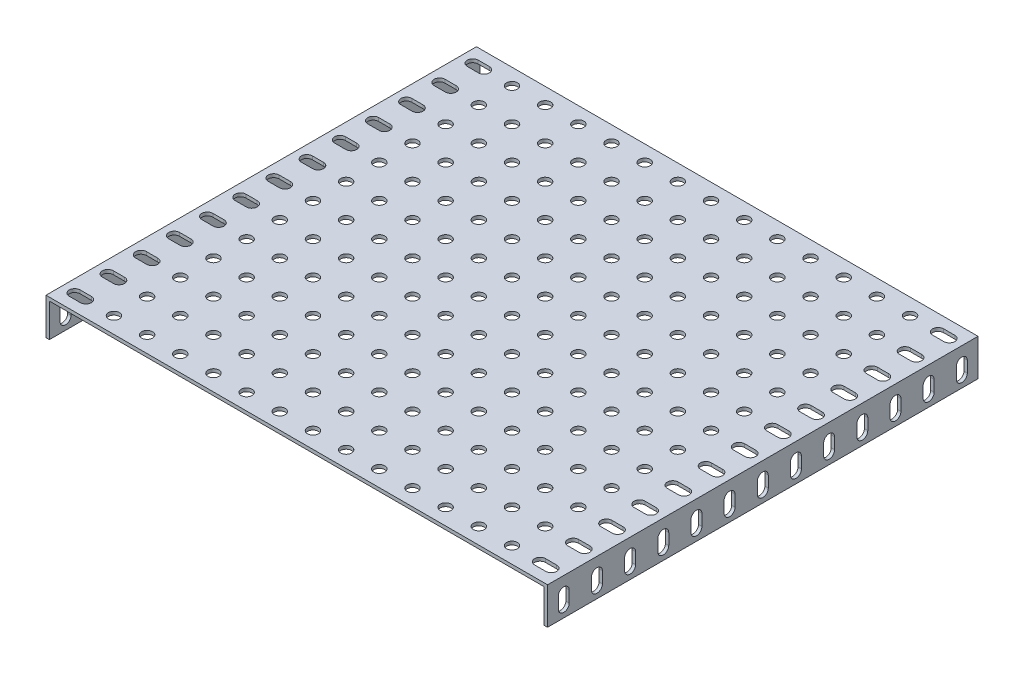
SolidWorks part; units mm, degrees
ref_plane "Front Plane" through (0, 0, 0) normal (0, 0, 1) x (1, 0, 0)
ref_plane "Top Plane" through (0, 0, 0) normal (0, 1, 0) x (1, 0, 0)
ref_plane "Right Plane" through (0, 0, 0) normal (1, 0, 0) x (0, 0, -1)
sketch "Sketch1" plane through (0, 0, 0) normal (0, 1, 0) x (1, 0, 0)
  line L0 (0, -76.56) -> (0, 76.56) construction
  line L1 (-91.66, 76.56) -> (-87.36, 76.56) construction
  line L2 (-91.66, 78.67) -> (-87.36, 78.67)
  line L3 (-91.66, 74.45) -> (-87.36, 74.45)
  line L4 (-91.66, 63.8) -> (-87.36, 63.8) construction
  line L5 (-91.66, 65.91) -> (-87.36, 65.91)
  line L6 (-91.66, 61.69) -> (-87.36, 61.69)
  line L7 (-91.66, 51.04) -> (-87.36, 51.04) construction
  line L8 (-91.66, 53.15) -> (-87.36, 53.15)
  line L9 (-91.66, 48.93) -> (-87.36, 48.93)
  line L10 (-91.66, 38.28) -> (-87.36, 38.28) construction
  line L11 (-91.66, 40.39) -> (-87.36, 40.39)
  line L12 (-91.66, 36.17) -> (-87.36, 36.17)
  line L13 (-91.66, 25.52) -> (-87.36, 25.52) construction
  line L14 (-91.66, 27.63) -> (-87.36, 27.63)
  line L15 (-91.66, 23.41) -> (-87.36, 23.41)
  line L16 (-91.66, 12.76) -> (-87.36, 12.76) construction
  line L17 (-91.66, 14.87) -> (-87.36, 14.87)
  line L18 (-91.66, 10.65) -> (-87.36, 10.65)
  line L19 (-91.66, 0) -> (-87.36, 0) construction
  line L20 (-91.66, 2.11) -> (-87.36, 2.11)
  line L21 (-91.66, -2.11) -> (-87.36, -2.11)
  line L22 (-91.66, -12.76) -> (-87.36, -12.76) construction
  line L23 (-91.66, -10.65) -> (-87.36, -10.65)
  line L24 (-91.66, -14.87) -> (-87.36, -14.87)
  line L25 (-91.66, -25.52) -> (-87.36, -25.52) construction
  line L26 (-91.66, -23.41) -> (-87.36, -23.41)
  line L27 (-91.66, -27.63) -> (-87.36, -27.63)
  line L28 (-91.66, -38.28) -> (-87.36, -38.28) construction
  line L29 (-91.66, -36.17) -> (-87.36, -36.17)
  line L30 (-91.66, -40.39) -> (-87.36, -40.39)
  line L31 (-91.66, -51.04) -> (-87.36, -51.04) construction
  line L32 (-91.66, -48.93) -> (-87.36, -48.93)
  line L33 (-91.66, -53.15) -> (-87.36, -53.15)
  line L34 (-91.66, -63.8) -> (-87.36, -63.8) construction
  line L35 (-91.66, -61.69) -> (-87.36, -61.69)
  line L36 (-91.66, -65.91) -> (-87.36, -65.91)
  line L37 (-91.66, -76.56) -> (-87.36, -76.56) construction
  line L38 (-91.66, -74.45) -> (-87.36, -74.45)
  line L39 (-91.66, -78.67) -> (-87.36, -78.67)
  line L40 (91.66, 76.56) -> (87.36, 76.56) construction
  line L41 (91.66, 78.67) -> (87.36, 78.67)
  line L42 (91.66, 74.45) -> (87.36, 74.45)
  line L43 (91.66, 63.8) -> (87.36, 63.8) construction
  line L44 (91.66, 65.91) -> (87.36, 65.91)
  line L45 (91.66, 61.69) -> (87.36, 61.69)
  line L46 (91.66, 51.04) -> (87.36, 51.04) construction
  line L47 (91.66, 53.15) -> (87.36, 53.15)
  line L48 (91.66, 48.93) -> (87.36, 48.93)
  line L49 (91.66, 38.28) -> (87.36, 38.28) construction
  line L50 (91.66, 40.39) -> (87.36, 40.39)
  line L51 (91.66, 36.17) -> (87.36, 36.17)
  line L52 (91.66, 25.52) -> (87.36, 25.52) construction
  line L53 (91.66, 27.63) -> (87.36, 27.63)
  line L54 (91.66, 23.41) -> (87.36, 23.41)
  line L55 (91.66, 12.76) -> (87.36, 12.76) construction
  line L56 (91.66, 14.87) -> (87.36, 14.87)
  line L57 (91.66, 10.65) -> (87.36, 10.65)
  line L58 (91.66, 0) -> (87.36, 0) construction
  line L59 (91.66, 2.11) -> (87.36, 2.11)
  line L60 (91.66, -2.11) -> (87.36, -2.11)
  line L61 (91.66, -12.76) -> (87.36, -12.76) construction
  line L62 (91.66, -10.65) -> (87.36, -10.65)
  line L63 (91.66, -14.87) -> (87.36, -14.87)
  line L64 (91.66, -25.52) -> (87.36, -25.52) construction
  line L65 (91.66, -23.41) -> (87.36, -23.41)
  line L66 (91.66, -27.63) -> (87.36, -27.63)
  line L67 (91.66, -38.28) -> (87.36, -38.28) construction
  line L68 (91.66, -36.17) -> (87.36, -36.17)
  line L69 (91.66, -40.39) -> (87.36, -40.39)
  line L70 (91.66, -51.04) -> (87.36, -51.04) construction
  line L71 (91.66, -48.93) -> (87.36, -48.93)
  line L72 (91.66, -53.15) -> (87.36, -53.15)
  line L73 (91.66, -63.8) -> (87.36, -63.8) construction
  line L74 (91.66, -61.69) -> (87.36, -61.69)
  line L75 (91.66, -65.91) -> (87.36, -65.91)
  line L76 (91.66, -76.56) -> (87.36, -76.56) construction
  line L77 (91.66, -74.45) -> (87.36, -74.45)
  line L78 (91.66, -78.67) -> (87.36, -78.67)
  line L80 (-93.77, 51.04) -> (-96.47, 51.04) construction
  line L81 (-96.47, 51.04) -> (-96.47, 82.79) construction
  line L83 (91.66, -78.67) -> (91.66, -82.79) construction
  line L84 (91.66, -82.79) -> (96.47, -82.79) construction
  line L86 (-96.47, 82.79) -> (96.47, 82.79)
  line L87 (-96.47, 82.79) -> (-96.47, -82.79)
  line L88 (-96.47, -82.79) -> (96.47, -82.79)
  line L89 (96.47, 82.79) -> (96.47, -82.79)
  circle A0 centre (-76.56, -76.56) radius 2.11
  circle A1 centre (-63.8, -76.56) radius 2.11
  circle A2 centre (-51.04, -76.56) radius 2.11
  circle A3 centre (-38.28, -76.56) radius 2.11
  circle A4 centre (-25.52, -76.56) radius 2.11
  circle A5 centre (-12.76, -76.56) radius 2.11
  circle A6 centre (0, -76.56) radius 2.11
  circle A7 centre (12.76, -76.56) radius 2.11
  circle A8 centre (25.52, -76.56) radius 2.11
  circle A9 centre (38.28, -76.56) radius 2.11
  circle A10 centre (51.04, -76.56) radius 2.11
  circle A11 centre (63.8, -76.56) radius 2.11
  circle A12 centre (76.56, -76.56) radius 2.11
  circle A13 centre (-63.8, -63.8) radius 2.11
  circle A14 centre (-51.04, -63.8) radius 2.11
  circle A15 centre (-38.28, -63.8) radius 2.11
  circle A16 centre (-25.52, -63.8) radius 2.11
  circle A17 centre (-12.76, -63.8) radius 2.11
  circle A18 centre (0, -63.8) radius 2.11
  circle A19 centre (12.76, -63.8) radius 2.11
  circle A20 centre (25.52, -63.8) radius 2.11
  circle A21 centre (38.28, -63.8) radius 2.11
  circle A22 centre (51.04, -63.8) radius 2.11
  circle A23 centre (63.8, -63.8) radius 2.11
  circle A24 centre (76.56, -63.8) radius 2.11
  circle A25 centre (-63.8, -51.04) radius 2.11
  circle A26 centre (-51.04, -51.04) radius 2.11
  circle A27 centre (-38.28, -51.04) radius 2.11
  circle A28 centre (-25.52, -51.04) radius 2.11
  circle A29 centre (-12.76, -51.04) radius 2.11
  circle A30 centre (0, -51.04) radius 2.11
  circle A31 centre (12.76, -51.04) radius 2.11
  circle A32 centre (25.52, -51.04) radius 2.11
  circle A33 centre (38.28, -51.04) radius 2.11
  circle A34 centre (51.04, -51.04) radius 2.11
  circle A35 centre (63.8, -51.04) radius 2.11
  circle A36 centre (76.56, -51.04) radius 2.11
  circle A37 centre (-63.8, -38.28) radius 2.11
  circle A38 centre (-51.04, -38.28) radius 2.11
  circle A39 centre (-38.28, -38.28) radius 2.11
  circle A40 centre (-25.52, -38.28) radius 2.11
  circle A41 centre (-12.76, -38.28) radius 2.11
  circle A42 centre (0, -38.28) radius 2.11
  circle A43 centre (12.76, -38.28) radius 2.11
  circle A44 centre (25.52, -38.28) radius 2.11
  circle A45 centre (38.28, -38.28) radius 2.11
  circle A46 centre (51.04, -38.28) radius 2.11
  circle A47 centre (63.8, -38.28) radius 2.11
  circle A48 centre (76.56, -38.28) radius 2.11
  circle A49 centre (-63.8, -25.52) radius 2.11
  circle A50 centre (-51.04, -25.52) radius 2.11
  circle A51 centre (-38.28, -25.52) radius 2.11
  circle A52 centre (-25.52, -25.52) radius 2.11
  circle A53 centre (-12.76, -25.52) radius 2.11
  circle A54 centre (0, -25.52) radius 2.11
  circle A55 centre (12.76, -25.52) radius 2.11
  circle A56 centre (25.52, -25.52) radius 2.11
  circle A57 centre (38.28, -25.52) radius 2.11
  circle A58 centre (51.04, -25.52) radius 2.11
  circle A59 centre (63.8, -25.52) radius 2.11
  circle A60 centre (76.56, -25.52) radius 2.11
  circle A61 centre (-63.8, -12.76) radius 2.11
  circle A62 centre (-51.04, -12.76) radius 2.11
  circle A63 centre (-38.28, -12.76) radius 2.11
  circle A64 centre (-25.52, -12.76) radius 2.11
  circle A65 centre (-12.76, -12.76) radius 2.11
  circle A66 centre (0, -12.76) radius 2.11
  circle A67 centre (12.76, -12.76) radius 2.11
  circle A68 centre (25.52, -12.76) radius 2.11
  circle A69 centre (38.28, -12.76) radius 2.11
  circle A70 centre (51.04, -12.76) radius 2.11
  circle A71 centre (63.8, -12.76) radius 2.11
  circle A72 centre (76.56, -12.76) radius 2.11
  circle A73 centre (-63.8, 0) radius 2.11
  circle A74 centre (-51.04, 0) radius 2.11
  circle A75 centre (-38.28, 0) radius 2.11
  circle A76 centre (-25.52, 0) radius 2.11
  circle A77 centre (-12.76, 0) radius 2.11
  circle A78 centre (0, 0) radius 2.11
  circle A79 centre (12.76, 0) radius 2.11
  circle A80 centre (25.52, 0) radius 2.11
  circle A81 centre (38.28, 0) radius 2.11
  circle A82 centre (51.04, 0) radius 2.11
  circle A83 centre (63.8, 0) radius 2.11
  circle A84 centre (76.56, 0) radius 2.11
  circle A85 centre (-63.8, 12.76) radius 2.11
  circle A86 centre (-51.04, 12.76) radius 2.11
  circle A87 centre (-38.28, 12.76) radius 2.11
  circle A88 centre (-25.52, 12.76) radius 2.11
  circle A89 centre (-12.76, 12.76) radius 2.11
  circle A90 centre (0, 12.76) radius 2.11
  circle A91 centre (12.76, 12.76) radius 2.11
  circle A92 centre (25.52, 12.76) radius 2.11
  circle A93 centre (38.28, 12.76) radius 2.11
  circle A94 centre (51.04, 12.76) radius 2.11
  circle A95 centre (63.8, 12.76) radius 2.11
  circle A96 centre (76.56, 12.76) radius 2.11
  circle A97 centre (-63.8, 25.52) radius 2.11
  circle A98 centre (-51.04, 25.52) radius 2.11
  circle A99 centre (-38.28, 25.52) radius 2.11
  circle A100 centre (-25.52, 25.52) radius 2.11
  circle A101 centre (-12.76, 25.52) radius 2.11
  circle A102 centre (0, 25.52) radius 2.11
  circle A103 centre (12.76, 25.52) radius 2.11
  circle A104 centre (25.52, 25.52) radius 2.11
  circle A105 centre (38.28, 25.52) radius 2.11
  circle A106 centre (51.04, 25.52) radius 2.11
  circle A107 centre (63.8, 25.52) radius 2.11
  circle A108 centre (76.56, 25.52) radius 2.11
  circle A109 centre (-63.8, 38.28) radius 2.11
  circle A110 centre (-51.04, 38.28) radius 2.11
  circle A111 centre (-38.28, 38.28) radius 2.11
  circle A112 centre (-25.52, 38.28) radius 2.11
  circle A113 centre (-12.76, 38.28) radius 2.11
  circle A114 centre (0, 38.28) radius 2.11
  circle A115 centre (12.76, 38.28) radius 2.11
  circle A116 centre (25.52, 38.28) radius 2.11
  circle A117 centre (38.28, 38.28) radius 2.11
  circle A118 centre (51.04, 38.28) radius 2.11
  circle A119 centre (63.8, 38.28) radius 2.11
  circle A120 centre (76.56, 38.28) radius 2.11
  circle A121 centre (-63.8, 51.04) radius 2.11
  circle A122 centre (-51.04, 51.04) radius 2.11
  circle A123 centre (-38.28, 51.04) radius 2.11
  circle A124 centre (-25.52, 51.04) radius 2.11
  circle A125 centre (-12.76, 51.04) radius 2.11
  circle A126 centre (0, 51.04) radius 2.11
  circle A127 centre (12.76, 51.04) radius 2.11
  circle A128 centre (25.52, 51.04) radius 2.11
  circle A129 centre (38.28, 51.04) radius 2.11
  circle A130 centre (51.04, 51.04) radius 2.11
  circle A131 centre (63.8, 51.04) radius 2.11
  circle A132 centre (76.56, 51.04) radius 2.11
  circle A133 centre (-63.8, 63.8) radius 2.11
  circle A134 centre (-51.04, 63.8) radius 2.11
  circle A135 centre (-38.28, 63.8) radius 2.11
  circle A136 centre (-25.52, 63.8) radius 2.11
  circle A137 centre (-12.76, 63.8) radius 2.11
  circle A138 centre (0, 63.8) radius 2.11
  circle A139 centre (12.76, 63.8) radius 2.11
  circle A140 centre (25.52, 63.8) radius 2.11
  circle A141 centre (38.28, 63.8) radius 2.11
  circle A142 centre (51.04, 63.8) radius 2.11
  circle A143 centre (63.8, 63.8) radius 2.11
  circle A144 centre (76.56, 63.8) radius 2.11
  circle A145 centre (-63.8, 76.56) radius 2.11
  circle A146 centre (-51.04, 76.56) radius 2.11
  circle A147 centre (-38.28, 76.56) radius 2.11
  circle A148 centre (-25.52, 76.56) radius 2.11
  circle A149 centre (-12.76, 76.56) radius 2.11
  circle A150 centre (0, 76.56) radius 2.11
  circle A151 centre (12.76, 76.56) radius 2.11
  circle A152 centre (25.52, 76.56) radius 2.11
  circle A153 centre (38.28, 76.56) radius 2.11
  circle A154 centre (51.04, 76.56) radius 2.11
  circle A155 centre (63.8, 76.56) radius 2.11
  circle A156 centre (76.56, 76.56) radius 2.11
  circle A157 centre (-76.56, -63.8) radius 2.11
  circle A158 centre (-76.56, -51.04) radius 2.11
  circle A159 centre (-76.56, -38.28) radius 2.11
  circle A160 centre (-76.56, -25.52) radius 2.11
  circle A161 centre (-76.56, -12.76) radius 2.11
  circle A162 centre (-76.56, 0) radius 2.11
  circle A163 centre (-76.56, 12.76) radius 2.11
  circle A164 centre (-76.56, 25.52) radius 2.11
  circle A165 centre (-76.56, 38.28) radius 2.11
  circle A166 centre (-76.56, 51.04) radius 2.11
  circle A167 centre (-76.56, 63.8) radius 2.11
  circle A168 centre (-76.56, 76.56) radius 2.11
  arc A169 (-91.66, 78.67) -> (-91.66, 74.45) centre (-91.66, 76.56) ccw
  arc A170 (-87.36, 74.45) -> (-87.36, 78.67) centre (-87.36, 76.56) ccw
  arc A171 (-91.66, 65.91) -> (-91.66, 61.69) centre (-91.66, 63.8) ccw
  arc A172 (-87.36, 61.69) -> (-87.36, 65.91) centre (-87.36, 63.8) ccw
  arc A173 (-91.66, 53.15) -> (-91.66, 48.93) centre (-91.66, 51.04) ccw
  arc A174 (-87.36, 48.93) -> (-87.36, 53.15) centre (-87.36, 51.04) ccw
  arc A175 (-91.66, 40.39) -> (-91.66, 36.17) centre (-91.66, 38.28) ccw
  arc A176 (-87.36, 36.17) -> (-87.36, 40.39) centre (-87.36, 38.28) ccw
  arc A177 (-91.66, 27.63) -> (-91.66, 23.41) centre (-91.66, 25.52) ccw
  arc A178 (-87.36, 23.41) -> (-87.36, 27.63) centre (-87.36, 25.52) ccw
  arc A179 (-91.66, 14.87) -> (-91.66, 10.65) centre (-91.66, 12.76) ccw
  arc A180 (-87.36, 10.65) -> (-87.36, 14.87) centre (-87.36, 12.76) ccw
  arc A181 (-91.66, 2.11) -> (-91.66, -2.11) centre (-91.66, 0) ccw
  arc A182 (-87.36, -2.11) -> (-87.36, 2.11) centre (-87.36, 0) ccw
  arc A183 (-91.66, -10.65) -> (-91.66, -14.87) centre (-91.66, -12.76) ccw
  arc A184 (-87.36, -14.87) -> (-87.36, -10.65) centre (-87.36, -12.76) ccw
  arc A185 (-91.66, -23.41) -> (-91.66, -27.63) centre (-91.66, -25.52) ccw
  arc A186 (-87.36, -27.63) -> (-87.36, -23.41) centre (-87.36, -25.52) ccw
  arc A187 (-91.66, -36.17) -> (-91.66, -40.39) centre (-91.66, -38.28) ccw
  arc A188 (-87.36, -40.39) -> (-87.36, -36.17) centre (-87.36, -38.28) ccw
  arc A189 (-91.66, -48.93) -> (-91.66, -53.15) centre (-91.66, -51.04) ccw
  arc A190 (-87.36, -53.15) -> (-87.36, -48.93) centre (-87.36, -51.04) ccw
  arc A191 (-91.66, -61.69) -> (-91.66, -65.91) centre (-91.66, -63.8) ccw
  arc A192 (-87.36, -65.91) -> (-87.36, -61.69) centre (-87.36, -63.8) ccw
  arc A193 (-91.66, -74.45) -> (-91.66, -78.67) centre (-91.66, -76.56) ccw
  arc A194 (-87.36, -78.67) -> (-87.36, -74.45) centre (-87.36, -76.56) ccw
  arc A195 (91.66, 78.67) -> (91.66, 74.45) centre (91.66, 76.56) cw
  arc A196 (87.36, 74.45) -> (87.36, 78.67) centre (87.36, 76.56) cw
  arc A197 (91.66, 65.91) -> (91.66, 61.69) centre (91.66, 63.8) cw
  arc A198 (87.36, 61.69) -> (87.36, 65.91) centre (87.36, 63.8) cw
  arc A199 (91.66, 53.15) -> (91.66, 48.93) centre (91.66, 51.04) cw
  arc A200 (87.36, 48.93) -> (87.36, 53.15) centre (87.36, 51.04) cw
  arc A201 (91.66, 40.39) -> (91.66, 36.17) centre (91.66, 38.28) cw
  arc A202 (87.36, 36.17) -> (87.36, 40.39) centre (87.36, 38.28) cw
  arc A203 (91.66, 27.63) -> (91.66, 23.41) centre (91.66, 25.52) cw
  arc A204 (87.36, 23.41) -> (87.36, 27.63) centre (87.36, 25.52) cw
  arc A205 (91.66, 14.87) -> (91.66, 10.65) centre (91.66, 12.76) cw
  arc A206 (87.36, 10.65) -> (87.36, 14.87) centre (87.36, 12.76) cw
  arc A207 (91.66, 2.11) -> (91.66, -2.11) centre (91.66, 0) cw
  arc A208 (87.36, -2.11) -> (87.36, 2.11) centre (87.36, 0) cw
  arc A209 (91.66, -10.65) -> (91.66, -14.87) centre (91.66, -12.76) cw
  arc A210 (87.36, -14.87) -> (87.36, -10.65) centre (87.36, -12.76) cw
  arc A211 (91.66, -23.41) -> (91.66, -27.63) centre (91.66, -25.52) cw
  arc A212 (87.36, -27.63) -> (87.36, -23.41) centre (87.36, -25.52) cw
  arc A213 (91.66, -36.17) -> (91.66, -40.39) centre (91.66, -38.28) cw
  arc A214 (87.36, -40.39) -> (87.36, -36.17) centre (87.36, -38.28) cw
  arc A215 (91.66, -48.93) -> (91.66, -53.15) centre (91.66, -51.04) cw
  arc A216 (87.36, -53.15) -> (87.36, -48.93) centre (87.36, -51.04) cw
  arc A217 (91.66, -61.69) -> (91.66, -65.91) centre (91.66, -63.8) cw
  arc A218 (87.36, -65.91) -> (87.36, -61.69) centre (87.36, -63.8) cw
  arc A219 (91.66, -74.45) -> (91.66, -78.67) centre (91.66, -76.56) cw
  arc A220 (87.36, -78.67) -> (87.36, -74.45) centre (87.36, -76.56) cw
  point P2 (-78.67, 76.56)
  point P3 (-89.51, 76.56)
  point P347 (-85.25, 76.56)
  point P348 (-2.11, 76.56)
  point P349 (-12.76, 74.45)
  point P350 (-89.51, 63.8)
  point P351 (-93.77, 76.56)
  point P358 (-89.51, 51.04)
  point P365 (-89.51, 38.28)
  point P372 (-89.51, 25.52)
  point P379 (-89.51, 12.76)
  point P386 (-89.51, 0)
  point P393 (-89.51, -12.76)
  point P400 (-89.51, -25.52)
  point P407 (-89.51, -38.28)
  point P414 (-89.51, -51.04)
  point P421 (-89.51, -63.8)
  point P428 (-89.51, -76.56)
  point P436 (-12.76, 65.91)
  point P437 (-10.65, 76.56)
  point P439 (89.51, 76.56)
  point P446 (89.51, 63.8)
  point P453 (89.51, 51.04)
  point P460 (89.51, 38.28)
  point P467 (89.51, 25.52)
  point P474 (89.51, 12.76)
  point P481 (89.51, 0)
  point P488 (89.51, -12.76)
  point P495 (89.51, -25.52)
  point P502 (89.51, -38.28)
  point P509 (89.51, -51.04)
  point P516 (89.51, -63.8)
  point P523 (89.51, -76.56)
  point P528 (93.77, 76.56)
  point P529 (85.25, 76.56)
  point P530 (-63.8, 78.67)
  point P531 (0, 0)
  point P533 (-93.77, 51.04)
  point P536 (93.77, -76.56)
  dimension "D1" = 4.22
  dimension "D4" = 6.58
  dimension "D5" = 4.22
  dimension "D6" = 8.52
  dimension "D7" = 8.54
  dimension "D9" = 8.54
  dimension "D10" = 8.54
  dimension "D11" = 4.12
  dimension "D12" = 2.7
  dimension "D13" = 2.7
  dimension "D14" = 4.12
  dimension "D2" = 13
  dimension "D3" = 13
  dimension "D8" = 13
extrude "Boss-Extrude1" add sketch "Sketch1" against normal blind 1.3
sketch "Sketch3" plane through (-96.47, 0, 0) normal (-1, 0, 0) x (0, 0, 1)
  line L0 (-76.56, -1.3) -> (-76.56, -14.16) construction
  line L1 (-82.79, 0) -> (82.79, 0)
  line L2 (-82.79, 0) -> (-82.79, -14.16)
  line L3 (-82.79, -14.16) -> (82.79, -14.16)
  line L4 (82.79, 0) -> (82.79, -14.16)
  line L5 (-76.56, -5.91) -> (-76.56, -10.21) construction
  line L6 (-74.45, -5.91) -> (-74.45, -10.21)
  line L7 (-78.67, -5.91) -> (-78.67, -10.21)
  line L11 (-82.79, -1.3) -> (82.79, -1.3) construction
  line L17 (-74.45, 0) -> (-78.67, 0) construction
  line L20 (-63.8, -5.91) -> (-63.8, -10.21) construction
  line L23 (-61.69, -5.91) -> (-61.69, -10.21)
  line L26 (-65.91, -5.91) -> (-65.91, -10.21)
  line L29 (-51.04, -5.91) -> (-51.04, -10.21) construction
  line L32 (-48.93, -5.91) -> (-48.93, -10.21)
  line L35 (-53.15, -5.91) -> (-53.15, -10.21)
  line L38 (-38.28, -5.91) -> (-38.28, -10.21) construction
  line L41 (-36.17, -5.91) -> (-36.17, -10.21)
  line L44 (-40.39, -5.91) -> (-40.39, -10.21)
  line L47 (-25.52, -5.91) -> (-25.52, -10.21) construction
  line L50 (-23.41, -5.91) -> (-23.41, -10.21)
  line L53 (-27.63, -5.91) -> (-27.63, -10.21)
  line L54 (-12.76, -5.91) -> (-12.76, -10.21) construction
  line L55 (-10.65, -5.91) -> (-10.65, -10.21)
  line L56 (-14.87, -5.91) -> (-14.87, -10.21)
  line L57 (0, -5.91) -> (0, -10.21) construction
  line L58 (2.11, -5.91) -> (2.11, -10.21)
  line L59 (-2.11, -5.91) -> (-2.11, -10.21)
  line L60 (12.76, -5.91) -> (12.76, -10.21) construction
  line L61 (14.87, -5.91) -> (14.87, -10.21)
  line L62 (10.65, -5.91) -> (10.65, -10.21)
  line L63 (25.52, -5.91) -> (25.52, -10.21) construction
  line L64 (27.63, -5.91) -> (27.63, -10.21)
  line L65 (23.41, -5.91) -> (23.41, -10.21)
  line L66 (38.28, -5.91) -> (38.28, -10.21) construction
  line L67 (40.39, -5.91) -> (40.39, -10.21)
  line L68 (36.17, -5.91) -> (36.17, -10.21)
  line L69 (51.04, -5.91) -> (51.04, -10.21) construction
  line L70 (53.15, -5.91) -> (53.15, -10.21)
  line L71 (48.93, -5.91) -> (48.93, -10.21)
  line L72 (63.8, -5.91) -> (63.8, -10.21) construction
  line L73 (65.91, -5.91) -> (65.91, -10.21)
  line L74 (61.69, -5.91) -> (61.69, -10.21)
  line L75 (76.56, -5.91) -> (76.56, -10.21) construction
  line L76 (78.67, -5.91) -> (78.67, -10.21)
  line L77 (74.45, -5.91) -> (74.45, -10.21)
  arc A0 (-74.45, -5.91) -> (-78.67, -5.91) centre (-76.56, -5.91) ccw
  arc A1 (-78.67, -10.21) -> (-74.45, -10.21) centre (-76.56, -10.21) ccw
  arc A32 (-61.69, -5.91) -> (-65.91, -5.91) centre (-63.8, -5.91) ccw
  arc A33 (-65.91, -10.21) -> (-61.69, -10.21) centre (-63.8, -10.21) ccw
  arc A34 (-48.93, -5.91) -> (-53.15, -5.91) centre (-51.04, -5.91) ccw
  arc A35 (-53.15, -10.21) -> (-48.93, -10.21) centre (-51.04, -10.21) ccw
  arc A36 (-36.17, -5.91) -> (-40.39, -5.91) centre (-38.28, -5.91) ccw
  arc A37 (-40.39, -10.21) -> (-36.17, -10.21) centre (-38.28, -10.21) ccw
  arc A38 (-23.41, -5.91) -> (-27.63, -5.91) centre (-25.52, -5.91) ccw
  arc A39 (-27.63, -10.21) -> (-23.41, -10.21) centre (-25.52, -10.21) ccw
  arc A40 (-10.65, -5.91) -> (-14.87, -5.91) centre (-12.76, -5.91) ccw
  arc A41 (-14.87, -10.21) -> (-10.65, -10.21) centre (-12.76, -10.21) ccw
  arc A42 (2.11, -5.91) -> (-2.11, -5.91) centre (0, -5.91) ccw
  arc A43 (-2.11, -10.21) -> (2.11, -10.21) centre (0, -10.21) ccw
  arc A44 (14.87, -5.91) -> (10.65, -5.91) centre (12.76, -5.91) ccw
  arc A45 (10.65, -10.21) -> (14.87, -10.21) centre (12.76, -10.21) ccw
  arc A46 (27.63, -5.91) -> (23.41, -5.91) centre (25.52, -5.91) ccw
  arc A47 (23.41, -10.21) -> (27.63, -10.21) centre (25.52, -10.21) ccw
  arc A48 (40.39, -5.91) -> (36.17, -5.91) centre (38.28, -5.91) ccw
  arc A49 (36.17, -10.21) -> (40.39, -10.21) centre (38.28, -10.21) ccw
  arc A50 (53.15, -5.91) -> (48.93, -5.91) centre (51.04, -5.91) ccw
  arc A51 (48.93, -10.21) -> (53.15, -10.21) centre (51.04, -10.21) ccw
  arc A52 (65.91, -5.91) -> (61.69, -5.91) centre (63.8, -5.91) ccw
  arc A53 (61.69, -10.21) -> (65.91, -10.21) centre (63.8, -10.21) ccw
  arc A54 (78.67, -5.91) -> (74.45, -5.91) centre (76.56, -5.91) ccw
  arc A55 (74.45, -10.21) -> (78.67, -10.21) centre (76.56, -10.21) ccw
  point P12 (-76.56, -8.06)
  point P18 (-76.56, -3.8)
  point P21 (-76.56, -12.32)
  point P22 (-63.8, -8.06)
  point P24 (-76.56, 0)
  point P31 (-51.04, -8.06)
  point P38 (-38.28, -8.06)
  point P45 (-25.52, -8.06)
  point P52 (-12.76, -8.06)
  point P59 (0, -8.06)
  point P66 (12.76, -8.06)
  point P73 (25.52, -8.06)
  point P80 (38.28, -8.06)
  point P87 (51.04, -8.06)
  point P94 (63.8, -8.06)
  point P101 (76.56, -8.06)
  point P109 (-78.67, -8.06)
  dimension "D1" = 14.16
  dimension "D2" = 3.8
  dimension "D3" = 8.52
  dimension "D4" = 4.22
  dimension "D6" = 8.54
  dimension "D5" = 13
extrude "Boss-Extrude2" add sketch "Sketch3" against normal blind 1.3
mirror "Mirror1" about plane through (0, 0, 0) normal (1, 0, 0) of "Boss-Extrude2"
